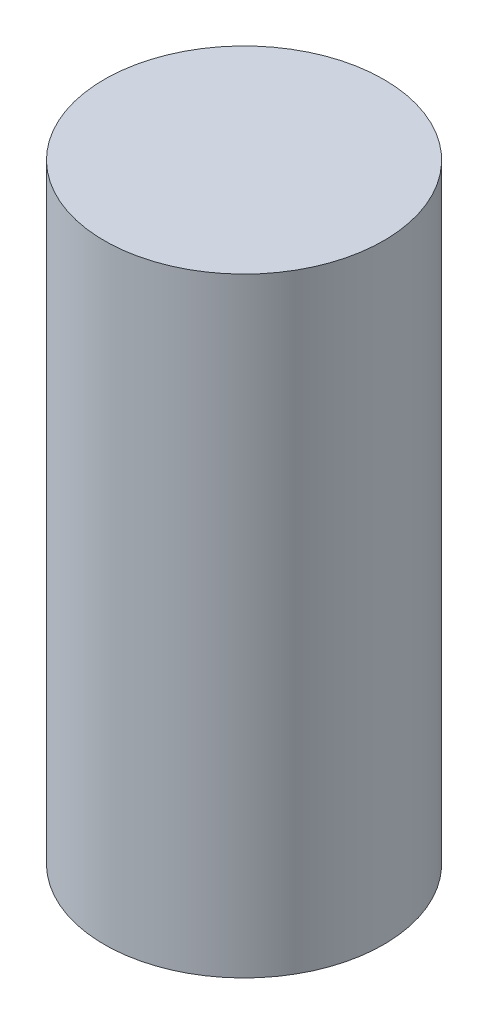
SolidWorks part; units mm, degrees
ref_plane "Front Plane" through (0, 0, 0) normal (0, 0, 1) x (1, 0, 0)
ref_plane "Top Plane" through (0, 0, 0) normal (0, 1, 0) x (1, 0, 0)
ref_plane "Right Plane" through (0, 0, 0) normal (1, 0, 0) x (0, 0, -1)
sketch "Sketch1" plane through (0, 0, 0) normal (0, 1, 0) x (1, 0, 0)
  circle A0 centre (0, 0) radius 1.49
  dimension "D1" = 2.98
extrude "Boss-Extrude1" add sketch "Sketch1" along normal blind 6.5
